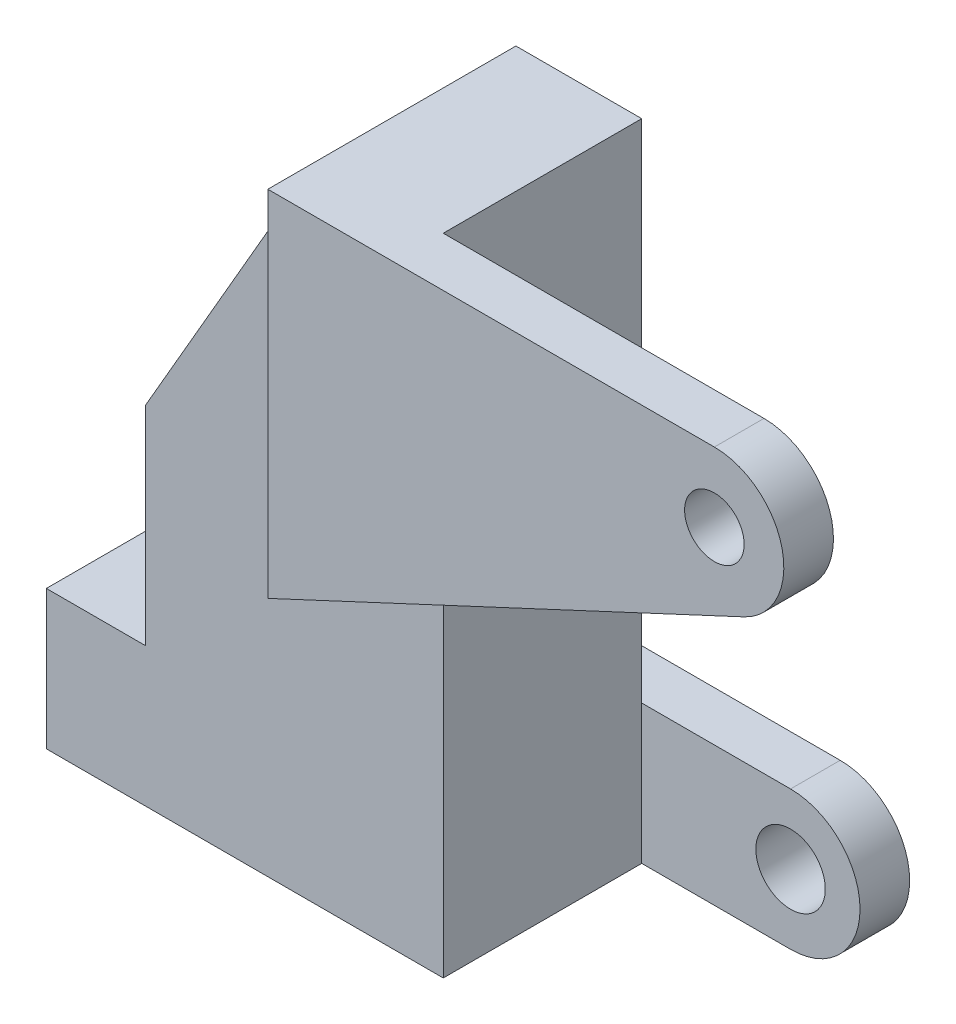
SolidWorks part; units mm, degrees
ref_plane "Front Plane" through (0, 0, 0) normal (0, 0, 1) x (1, 0, 0)
ref_plane "Top Plane" through (0, 0, 0) normal (0, 1, 0) x (1, 0, 0)
ref_plane "Right Plane" through (0, 0, 0) normal (1, 0, 0) x (0, 0, -1)
sketch "Sketch1" plane through (0, 0, 0) normal (0, 0, 1) x (1, 0, 0)
  line L0 (0, 0) -> (0, 14)
  line L1 (0, 14) -> (10, 14)
  line L2 (10, 14) -> (10, 35)
  line L3 (10, 35) -> (27.3205, 65)
  line L4 (27.3205, 65) -> (40, 65)
  line L5 (40, 65) -> (40, 0)
  line L6 (40, 0) -> (0, 0)
  point P3 (25.5093, 60.6056)
  dimension "D1" = 40
  dimension "D2" = 30
  dimension "D3" = 35
  dimension "D4" = 65
  dimension "D5" = 10
  dimension "D6" = 14
extrude "Boss-Extrude1" add sketch "Sketch1" along normal blind 20
sketch "Sketch2" plane through (0, 0, 20) normal (0, 0, 1) x (1, 0, 0)
  line L0 (27.3205, 65) -> (27.3205, 29.2925)
  line L1 (27.3205, 29.2925) -> (75.2788, 51.6558)
  line L2 (72.3205, 65) -> (27.3205, 65)
  arc A0 (75.2788, 51.6558) -> (72.3205, 65) centre (72.3205, 58) ccw
  circle A1 centre (72.3205, 58) radius 3
  dimension "D2" = 7
  dimension "D4" = 6
  dimension "D1" = 45
  dimension "D3" = 65
extrude "Boss-Extrude2" add sketch "Sketch2" along normal blind 5
sketch "Sketch3" plane through (0, 0, 0) normal (0, 0, -1) x (-1, 0, 0)
  line L0 (-10, 14) -> (-10, 0)
  line L1 (0, 0) -> (-40, 0) construction
  line L2 (-10, 0) -> (-55, 0)
  line L3 (-55, 14) -> (-10, 14)
  line L4 (-40, 0) -> (-40, 65) construction
  arc A0 (-55, 0) -> (-55, 14) centre (-55, 7) cw
  circle A1 centre (-55, 7) radius 3.5
  dimension "D1" = 7
  dimension "D2" = 7
  dimension "D3" = 15
extrude "Boss-Extrude3" add sketch "Sketch3" along normal blind 5
